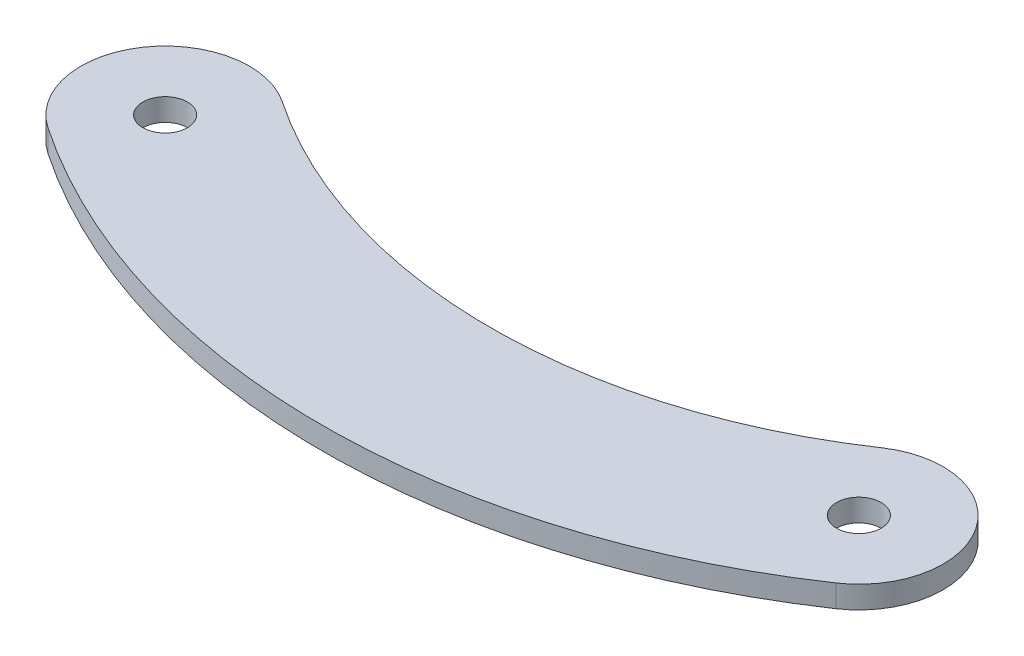
SolidWorks part; units mm, degrees
ref_plane "Front Plane" through (0, 0, 0) normal (0, 0, 1) x (1, 0, 0)
ref_plane "Top Plane" through (0, 0, 0) normal (0, 1, 0) x (1, 0, 0)
ref_plane "Right Plane" through (0, 0, 0) normal (1, 0, 0) x (0, 0, -1)
sketch "Sketch1" plane through (0, 0, 0) normal (0, 1, 0) x (1, 0, 0)
  line L0 (-24.672, 0) -> (24.672, 0) construction
  line L1 (0, 36.6142) -> (-24.672, 0) construction
  line L3 (-24.672, 0) -> (-28.0249, -4.9758) construction
  line L5 (30.672, -6) -> (-30.672, 6) construction
  line L6 (30.672, 6) -> (-30.672, -6) construction
  line L7 (0, 36.6142) -> (24.672, 0) construction
  line L8 (24.672, 0) -> (28.0249, -4.9758) construction
  circle A0 centre (-24.672, 0) radius 1.5875
  circle A1 centre (24.672, 0) radius 1.5875
  circle A2 centre (-24.672, 0) radius 5 construction
  circle A3 centre (0, 36.6142) radius 44.151 construction
  arc A4 (-21.3191, 4.9758) -> (21.3191, 4.9758) centre (0, 36.6142) ccw
  arc A5 (-28.0249, -4.9758) -> (28.0249, -4.9758) centre (0, 36.6142) ccw
  arc A6 (-21.3191, 4.9758) -> (-28.0249, -4.9758) centre (-24.672, 0) ccw
  arc A7 (28.0249, -4.9758) -> (21.3191, 4.9758) centre (24.672, 0) ccw
  point P0 (0, 0)
  point P8 (0, 0)
  dimension "D1" = 3.175
  dimension "D4" = 10
  dimension "D6" = 6
  dimension "D7" = 6
  dimension "D2" = 49.344
  dimension "D3" = 12
extrude "Boss-Extrude1" add sketch "Sketch1" along normal mid plane 1.5875
